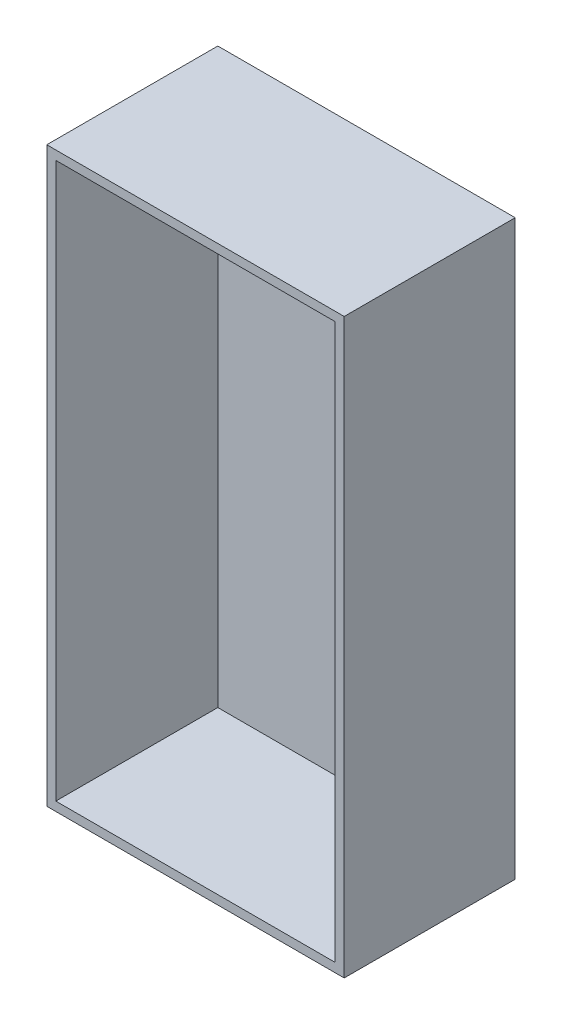
SolidWorks part; units mm, degrees
material "ABS"
ref_plane "X-Y Datum" through (0, 0, 0) normal (0, 0, 1) x (1, 0, 0)
ref_plane "X-Z Datum" through (0, 0, 0) normal (0, 1, 0) x (1, 0, 0)
ref_plane "Y-Z Datum" through (0, 0, 0) normal (1, 0, 0) x (0, 0, -1)
sketch "Sketch6" plane through (0, 0, 0) normal (0, 0, 1) x (1, 0, 0)
  line L0 (-12.5134, -74.0435) -> (88.5786, -74.0435) construction
  line L6 (-12.5134, -1.9075) -> (88.5786, -1.9075) construction
  line L7 (88.5786, -74.0435) -> (88.5786, -1.9075) construction
  line L8 (-57.9089, 111.2495) -> (4.5751, 111.2495) construction
  line L9 (-57.9089, 111.2495) -> (-57.9089, 1.9025) construction
  line L10 (-57.9089, 1.9025) -> (4.5751, 1.9025) construction
  line L11 (4.5751, 111.2495) -> (4.5751, 1.9025) construction
  line L12 (88.2023, 1.9025) -> (8.3851, 1.9025) construction
  line L13 (88.2023, 1.9025) -> (88.2023, 145.7849) construction
  line L14 (88.2023, 145.7849) -> (8.3851, 145.7849) construction
  line L15 (8.3851, 1.9025) -> (8.3851, 145.7849) construction
  line L16 (88.2023, 1.9025) -> (8.3851, 145.7849) construction
  line L17 (88.2023, 145.7849) -> (8.3851, 1.9025) construction
  line L18 (-59.1789, 112.5195) -> (5.8451, 112.5195)
  line L23 (-35.0564, -1.9075) -> (-12.5134, -1.9075) construction
  line L24 (-35.0564, -1.9075) -> (-35.0564, -74.0435) construction
  line L25 (-35.0564, -74.0435) -> (-12.5134, -74.0435) construction
  line L27 (5.8451, 112.5195) -> (5.8451, 0.6325)
  line L28 (-59.1789, 0.6325) -> (5.8451, 0.6325)
  line L29 (-59.1789, 112.5195) -> (-59.1789, 0.6325)
  line L30 (-12.5134, -0.6375) -> (89.8486, -0.6375)
  line L31 (89.8486, -75.3135) -> (89.8486, -0.6375)
  line L32 (-12.5134, -75.3135) -> (89.8486, -75.3135)
  line L33 (-36.3264, -75.3135) -> (-12.5134, -75.3135)
  line L34 (-36.3264, -0.6375) -> (-36.3264, -75.3135)
  line L35 (-36.3264, -0.6375) -> (-12.5134, -0.6375)
  line L36 (89.4723, 147.0549) -> (7.1151, 147.0549)
  line L37 (7.1151, 0.6325) -> (7.1151, 147.0549)
  line L38 (89.4723, 0.6325) -> (7.1151, 0.6325)
  line L39 (89.4723, 0.6325) -> (89.4723, 147.0549)
  circle A0 centre (-6.4174, -7.8841) radius 2.1
  circle A1 centre (82.9906, -6.8681) radius 2.1
  circle A2 centre (82.8086, -67.8271) radius 2.1
  circle A3 centre (-7.4334, -68.8441) radius 2.1
  circle A4 centre (-54.3765, 106.4235) radius 2.1
  circle A5 centre (-2.3085, 106.4425) radius 2.1
  circle A6 centre (-2.4335, 6.7285) radius 2.1
  circle A7 centre (-54.3765, 6.7285) radius 2.1
  circle A8 centre (48.2937, 118.2849) radius 27.5
  circle A9 centre (48.347, 29.3848) radius 27.5
  circle A10 centre (38.1604, 73.8437) radius 6.477
  circle A11 centre (58.4804, 73.826) radius 6.477
  circle A12 centre (14.8621, 92.914) radius 6.477
  circle A13 centre (20.3804, 73.8592) radius 2.4
  circle A14 centre (76.2603, 73.8105) radius 2.4
  point P43 (48.2937, 73.8437)
  dimension "D1" = 109.347
  dimension "D2" = 62.484
  dimension "D3" = 79.8172
  dimension "D4" = 143.8823
  dimension "D5" = 101.092
  dimension "D6" = 72.136
  dimension "D10" = 1.27
  dimension "D11" = 1.27
  dimension "D7" = 1.27
  dimension "D8" = 1.27
  dimension "D9" = 1.27
sketch "Sketch7" plane through (0, 0, 0) normal (0, 0, 1) x (1, 0, 0)
  line L1 (89.4723, 147.0549) -> (89.7853, -37.8829) construction
  line L2 (26.7611, -75.3135) -> (-36.3264, -75.3135) construction
  line L4 (75.7937, 118.2849) -> (75.7937, 145.7849) construction
  line L19 (48.347, 1.8848) -> (75.847, 1.9025) construction
  line L20 (88.2023, 145.7849) -> (8.3851, 145.7849) construction
  line L21 (75.7937, 145.7849) -> (48.2937, 145.7849) construction
  line L22 (88.2023, 1.9025) -> (8.3851, 1.9025) construction
  line L23 (75.847, 1.9025) -> (75.847, 29.3848) construction
  line L24 (8.3851, 92.914) -> (3.3051, 92.914) construction
  line L25 (9.6551, 152.1349) -> (82.1437, 152.1349)
  line L27 (26.7611, -75.3135) -> (26.7611, -76.5835) construction
  line L28 (82.1437, 152.1349) -> (82.1437, -4.4475)
  line L29 (82.1437, -4.4475) -> (14.497, -4.4475)
  line L30 (8.3851, 1.9025) -> (8.3851, 145.7849) construction
  line L31 (3.3051, 92.914) -> (3.3051, 152.1349)
  line L32 (3.3051, 152.1349) -> (9.6551, 152.1349)
  line L33 (3.3051, 92.914) -> (3.3051, -4.4475)
  line L34 (3.3051, -4.4475) -> (14.497, -4.4475)
  line L35 (69.4437, 145.7849) -> (69.4437, 152.1349)
  line L36 (75.7937, 97.1349) -> (82.1437, 97.1349) construction
  line L37 (75.7937, 84.4349) -> (82.1437, 84.4349) construction
  line L38 (75.847, 63.2348) -> (82.1437, 63.2348) construction
  line L39 (75.847, 8.2525) -> (82.1437, 8.2525) construction
  line L40 (9.6551, 62.926) -> (3.3051, 62.926) construction
  line L41 (9.6551, 50.226) -> (3.3051, 50.226) construction
  line L42 (16.0051, 145.7849) -> (16.0051, 152.1349) construction
  line L44 (16.0051, 1.9025) -> (16.0051, -4.4475) construction
  line L45 (69.497, 1.9025) -> (69.497, -4.4475) construction
  line L46 (9.6551, 139.4349) -> (3.3051, 139.4349) construction
  line L48 (75.7937, 139.4349) -> (82.1437, 139.4349) construction
  line L49 (9.6551, 8.2525) -> (3.3051, 8.2525) construction
  circle A23 centre (75.7937, 145.7849) radius 6.35 construction
  circle A24 centre (48.2937, 118.2849) radius 27.5 construction
  circle A25 centre (48.347, 29.3848) radius 27.5 construction
  circle A26 centre (75.847, 1.9025) radius 6.35 construction
  circle A27 centre (75.7937, 90.7849) radius 6.35 construction
  circle A28 centre (75.847, 56.8848) radius 6.35 construction
  circle A29 centre (9.6551, 56.576) radius 6.35 construction
  circle A30 centre (9.6551, 1.9025) radius 6.35 construction
  circle A31 centre (9.6551, 145.7849) radius 6.35 construction
  circle A32 centre (14.8621, 92.914) radius 6.477 construction
extrude "Boss-Extrude1" add sketch "Sketch7" along normal blind 45.72 contours L29 L34 L33 L31 L32 L25 L28
shell "Shell1" thickness 2.54
sketch "Sketch8" plane through (0, 0, -2.54) normal (0, 0, -1) x (-1, 0, 0)
  line L0 (-257.232, -11.9929) -> (-156.14, -11.9929) construction
  line L1 (-257.232, -11.9929) -> (-257.232, 60.1431) construction
  line L2 (-257.232, 60.1431) -> (-156.14, 60.1431) construction
  line L3 (-156.14, -11.9929) -> (-156.14, 60.1431) construction
  line L4 (-257.232, 60.1431) -> (-279.7752, 60.1431) construction
  line L5 (-257.232, 60.1431) -> (-257.232, -11.9929) construction
  line L6 (-257.232, -11.9929) -> (-279.7752, -11.9929) construction
  line L7 (-279.7752, 60.1431) -> (-279.7752, -11.9929) construction
  line L9 (-97.3979, 99.1845) -> (-97.3979, 161.6685)
  line L10 (-97.3979, 99.1845) -> (11.9491, 99.1845)
  line L11 (11.9491, 99.1845) -> (11.9491, 161.6685)
  line L12 (-97.3979, 161.6685) -> (11.9491, 161.6685)
  line L13 (-0.7651, 154.6749) -> (-84.6837, 154.6749) construction
  circle A0 centre (-251.136, 54.0471) radius 2.1 construction
  circle A1 centre (-161.728, 55.0631) radius 2.1 construction
  circle A2 centre (-161.91, -5.8959) radius 2.1 construction
  circle A3 centre (-252.152, -6.9129) radius 2.1 construction
  circle A4 centre (-92.5719, 103.9343) radius 2.1
  circle A5 centre (-92.5909, 156.0023) radius 2.1
  circle A6 centre (7.1231, 155.8773) radius 2.1
  circle A7 centre (7.1231, 103.9343) radius 2.1
  point P29 (-42.7244, 154.6749)
